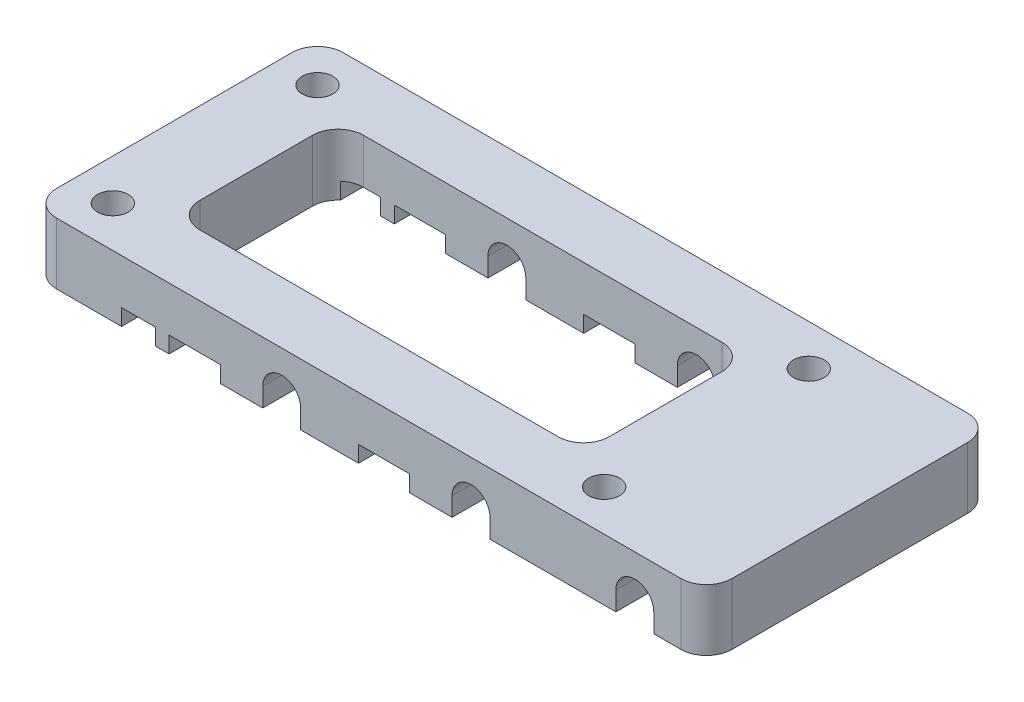
SolidWorks part; units mm, degrees
ref_plane "Front Plane" through (0, 0, 0) normal (0, 0, 1) x (1, 0, 0)
ref_plane "Top Plane" through (0, 0, 0) normal (0, 1, 0) x (1, 0, 0)
ref_plane "Right Plane" through (0, 0, 0) normal (1, 0, 0) x (0, 0, -1)
sketch "Sketch1" plane through (0, 0, 0) normal (0, 1, 0) x (1, 0, 0)
  line L0 (30.48, 12.7) -> (30.48, 17.78) construction
  line L1 (-30.48, 12.7) -> (30.48, 12.7) construction
  line L2 (-30.48, 12.7) -> (-30.48, -12.7) construction
  line L3 (-30.48, -12.7) -> (30.48, -12.7) construction
  line L4 (30.48, 12.7) -> (30.48, -12.7) construction
  line L5 (-30.48, 12.7) -> (30.48, -12.7) construction
  line L6 (-30.48, -12.7) -> (30.48, 12.7) construction
  line L7 (-35.56, 17.78) -> (35.56, 17.78)
  line L8 (-35.56, 17.78) -> (-35.56, -17.78)
  line L9 (-35.56, -17.78) -> (35.56, -17.78)
  line L10 (35.56, 17.78) -> (35.56, -17.78)
  line L11 (-35.56, 17.78) -> (35.56, -17.78) construction
  line L12 (-35.56, -17.78) -> (35.56, 17.78) construction
  line L13 (-25.4, 10.16) -> (25.4, 10.16)
  line L14 (-25.4, 10.16) -> (-25.4, -10.16)
  line L15 (-25.4, -10.16) -> (25.4, -10.16)
  line L16 (25.4, 10.16) -> (25.4, -10.16)
  line L17 (-25.4, 10.16) -> (25.4, -10.16) construction
  line L18 (-25.4, -10.16) -> (25.4, 10.16) construction
  line L19 (30.48, -12.7) -> (30.48, -17.78) construction
  circle A0 centre (30.48, 12.7) radius 1.905
  circle A1 centre (-30.48, 12.7) radius 1.905
  circle A2 centre (-30.48, -12.7) radius 1.905
  circle A3 centre (30.48, -12.7) radius 1.905
  point P0 (0, 0)
  point P10 (0, 0)
  point P15 (0, 0)
  dimension "D3" = 3.81
  dimension "D1" = 60.96
  dimension "D2" = 25.4
  dimension "D4" = 35.56
  dimension "D5" = 71.12
  dimension "D6" = 20.32
  dimension "D7" = 50.8
extrude "Boss-Extrude1" add sketch "Sketch1" along normal blind 7.62
sketch "Sketch3" plane through (35.56, 0, 0) normal (1, 0, 0) x (0, 0, -1)
  line L0 (17.78, 7.62) -> (17.78, 0) construction
  line L1 (-17.78, 0) -> (17.78, 0) construction
  line L2 (-17.78, 7.62) -> (-17.78, 0) construction
  line L3 (-17.78, 7.62) -> (17.78, 7.62) construction
  line L4 (17.78, 7.62) -> (17.78, 0)
  line L5 (-17.78, 0) -> (17.78, 0)
  line L6 (-17.78, 7.62) -> (-17.78, 0)
  line L7 (-17.78, 7.62) -> (17.78, 7.62)
extrude "Boss-Extrude2" add sketch "Sketch3" along normal blind 12.7
sketch "Sketch2" plane through (0, 0, 17.78) normal (0, 0, 1) x (1, 0, 0)
  line L0 (19.05, 0) -> (19.05, 2.3495) construction
  line L1 (-35.56, 0) -> (48.26, 0) construction
  line L2 (8.255, 0) -> (8.255, 1.016) construction
  line L3 (-4.445, 0) -> (-4.445, 2.3495) construction
  line L4 (-15.24, 0) -> (-15.24, 1.016) construction
  line L5 (21.3995, 2.3495) -> (21.3995, 0)
  line L6 (21.3995, 0) -> (16.7005, 0)
  line L7 (16.7005, 0) -> (16.7005, 2.3495)
  line L9 (21.3995, 2.3495) -> (19.05, 2.3495) construction
  line L10 (-2.0955, 2.3495) -> (-2.0955, 0)
  line L11 (-2.0955, 0) -> (-6.7945, 0)
  line L12 (-6.7945, 0) -> (-6.7945, 2.3495)
  line L14 (5.08, 2.032) -> (11.43, 2.032)
  line L15 (5.08, 2.032) -> (5.08, 0)
  line L16 (5.08, 0) -> (11.43, 0)
  line L17 (11.43, 2.032) -> (11.43, 0)
  line L18 (5.08, 2.032) -> (11.43, 0) construction
  line L19 (5.08, 0) -> (11.43, 2.032) construction
  line L20 (-18.415, 2.032) -> (-12.065, 2.032)
  line L21 (-18.415, 2.032) -> (-18.415, 0)
  line L22 (-18.415, 0) -> (-12.065, 0)
  line L23 (-12.065, 2.032) -> (-12.065, 0)
  line L24 (-18.415, 2.032) -> (-12.065, 0) construction
  line L25 (-18.415, 0) -> (-12.065, 2.032) construction
  line L26 (30.48, 0) -> (39.37, 0) construction
  line L27 (-35.56, 0) -> (48.26, 0) construction
  line L28 (39.37, 0) -> (48.26, 0) construction
  line L29 (39.37, 0) -> (39.37, 2.3495) construction
  line L30 (41.7195, 2.3495) -> (41.7195, 0)
  line L31 (41.7195, 0) -> (37.0205, 0)
  line L32 (37.0205, 0) -> (37.0205, 2.3495)
  line L33 (41.7195, 2.3495) -> (39.37, 2.3495) construction
  line L35 (-20.1295, 2.032) -> (-24.3205, 2.032)
  line L36 (-20.1295, 2.032) -> (-20.1295, 0)
  line L37 (-20.1295, 0) -> (-24.3205, 0)
  line L38 (-24.3205, 2.032) -> (-24.3205, 0)
  line L39 (-20.1295, 2.032) -> (-24.3205, 0) construction
  line L40 (-20.1295, 0) -> (-24.3205, 2.032) construction
  arc A0 (21.3995, 2.3495) -> (16.7005, 2.3495) centre (19.05, 2.3495) ccw
  arc A1 (-2.0955, 2.3495) -> (-6.7945, 2.3495) centre (-4.445, 2.3495) ccw
  arc A2 (41.7195, 2.3495) -> (37.0205, 2.3495) centre (39.37, 2.3495) ccw
  point P28 (30.48, 0)
  point P32 (-22.225, 1.016)
  dimension "D1" = 4.699
  dimension "D2" = 11.43
  dimension "D3" = 22.225
  dimension "D4" = 6.35
  dimension "D5" = 2.032
  dimension "D6" = 34.925
  dimension "D7" = 45.72
  dimension "D8" = 4.191
  dimension "D9" = 52.705
extrude "Cut-Extrude1" cut sketch "Sketch2" against normal through all
fillet "Fillet1" radius 3.175 8 edges at (-35.56, 3.81, -17.78) (-35.56, 3.81, 17.78) (48.26, 3.81, -17.78) (48.26, 3.81, 17.78) (25.4, 3.81, 10.16) (25.4, 3.81, -10.16) (-25.4, 3.81, -10.16) (-25.4, 3.81, 10.16)
